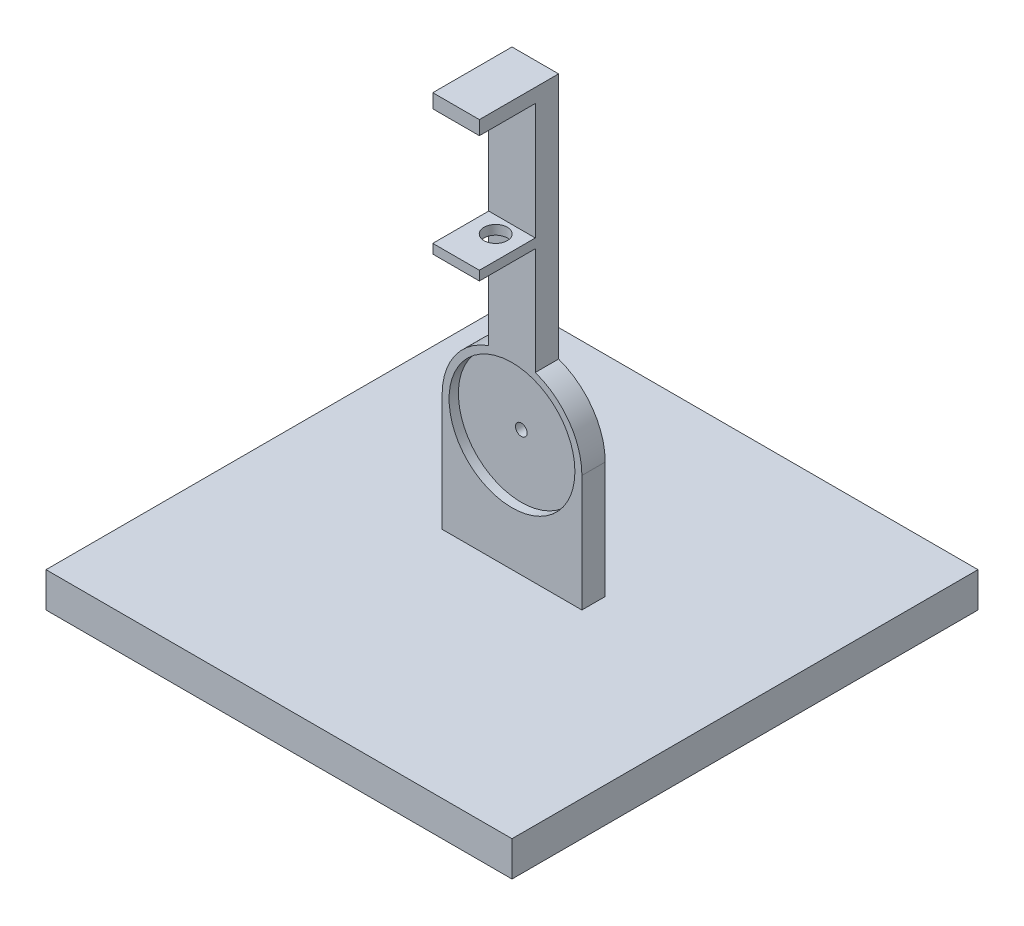
SolidWorks part; units mm, degrees
ref_plane "Front Plane" through (0, 0, 0) normal (0, 0, 1) x (1, 0, 0)
ref_plane "Top Plane" through (0, 0, 0) normal (0, 1, 0) x (1, 0, 0)
ref_plane "Right Plane" through (0, 0, 0) normal (1, 0, 0) x (0, 0, -1)
sketch "Sketch1" plane through (0, 0, 0) normal (0, 0, 1) x (1, 0, 0)
  line L1 (0, 0) -> (100, 0)
  line L2 (0, 0) -> (0, 7.5)
  line L3 (0, 7.5) -> (100, 7.5)
  line L4 (100, 0) -> (100, 7.5)
  dimension "D1" = 7.5
  dimension "D2" = 100
extrude "Boss-Extrude1" add sketch "Sketch1" along normal blind 100 contours L3 L4 L1 L2
sketch "Sketch2" plane through (0, 0, 0) normal (0, 0, 1) x (1, 0, 0)
  line L0 (0, 7.5) -> (100, 7.5) construction
  line L1 (35, 7.5) -> (65, 7.5)
  line L2 (35, 7.5) -> (35, 32.5)
  line L4 (65, 7.5) -> (65, 32.5)
  line L5 (50, 22.2757) -> (50, 11.3147) construction
  line L6 (100, 0) -> (100, 7.5) construction
  line L9 (45, 46.6421) -> (45, 96.6421)
  line L10 (45, 96.6421) -> (55, 96.6421)
  line L11 (55, 46.6421) -> (55, 96.6421)
  arc A0 (35, 32.5) -> (45, 46.6421) centre (50, 32.5) cw
  arc A1 (55, 46.6421) -> (65, 32.5) centre (50, 32.5) cw
  dimension "D4" = 50
  dimension "D1" = 25
  dimension "D2" = 30
  dimension "D3" = 50
  dimension "D5" = 10
extrude "Boss-Extrude2" add sketch "Sketch2" along normal blind 5 from offset 45 contours L2 A0 L9 L10 L11 A1 L4 L1
sketch "Sketch3" plane through (0, 0, 50) normal (0, 0, 1) x (1, 0, 0)
  circle A0 centre (50, 32.5) radius 13.5
  dimension "D1" = 27
extrude "Cut-Extrude1" cut sketch "Sketch3" against normal blind 2 contours A0
sketch "Sketch4" plane through (0, 0, 45) normal (0, 0, -1) x (-1, 0, 0)
  line L0 (-45, 46.6421) -> (-45, 96.6421) construction
  line L1 (-55, 96.6421) -> (-45, 96.6421)
  line L2 (-55, 96.6421) -> (-55, 99.6421)
  line L3 (-55, 99.6421) -> (-45, 99.6421)
  line L4 (-45, 96.6421) -> (-45, 99.6421)
  dimension "D1" = 3
extrude "Boss-Extrude3" add sketch "Sketch4" against normal blind 17 contours L3 L4 L1 L2
ref_plane "Plane1" through (0, 71.6421, 0) normal (0, -1, 0) x (-1, 0, 0)
sketch "Sketch6" plane through (0, 71.6421, 0) normal (0, -1, 0) x (-1, 0, 0)
  line L0 (-35, -50) -> (-65, -50) construction
  line L1 (-55, -62) -> (-45, -62) construction
  line L2 (-55, -62) -> (-55, -45) construction
  line L3 (-45, -62) -> (-45, -45) construction
  line L4 (-45, -50) -> (-55, -50)
  line L5 (-55, -62) -> (-45, -62)
  line L6 (-55, -62) -> (-55, -50)
  line L7 (-45, -62) -> (-45, -50)
  circle A0 centre (-50, -53.5) radius 2.5
  dimension "D1" = 5
  dimension "D2" = 5
  dimension "D3" = 3.5
extrude "Boss-Extrude4" add sketch "Sketch6" along normal blind 2 contours L5 L7 L4 L6 A0
sketch "Sketch7" plane through (0, 0, 48) normal (0, 0, 1) x (1, 0, 0)
  circle A0 centre (50, 32.5) radius 1.25
  dimension "D1" = 2.5
extrude "Cut-Extrude2" cut sketch "Sketch7" against normal up to next
